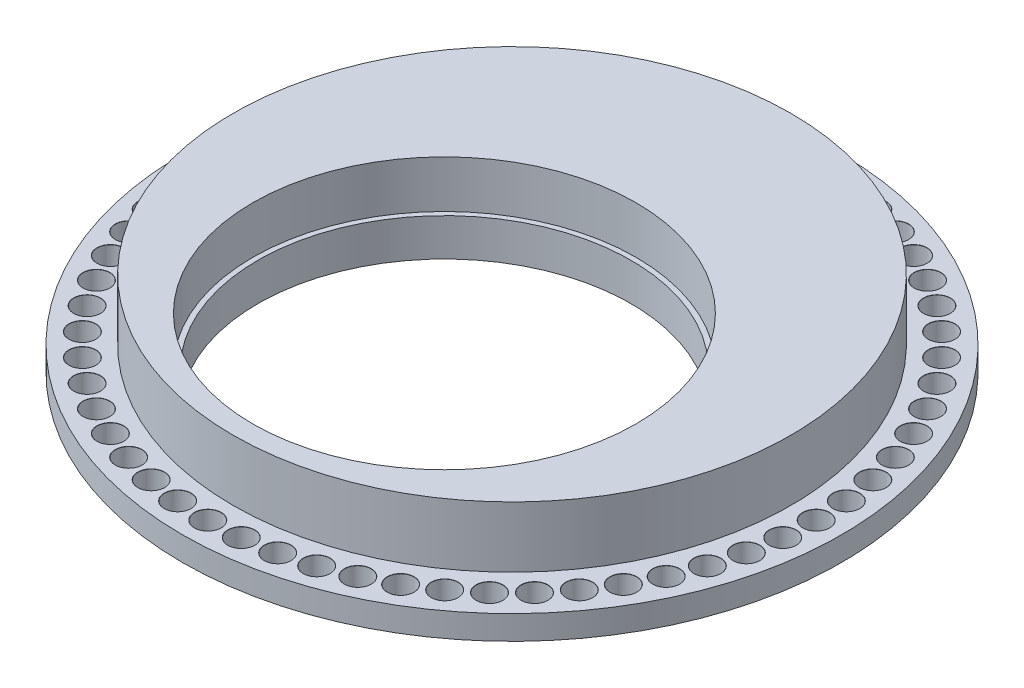
SolidWorks part; units mm, degrees
material "7075-T6, Plate (SS)"
ref_plane "X-Y Datum" through (0, 0, 0) normal (0, 0, 1) x (1, 0, 0)
ref_plane "X-Z Datum" through (0, 0, 0) normal (0, 1, 0) x (1, 0, 0)
ref_plane "Y-Z Datum" through (0, 0, 0) normal (1, 0, 0) x (0, 0, -1)
sketch "Sketch1" plane through (0, 0, 0) normal (0, 1, 0) x (1, 0, 0)
  line L0 (0, 0) -> (0, -12.7) construction
  line L1 (0, -43.0151) -> (0, 43.0151) construction
  line L2 (0, 61.9125) -> (0, 52.3875)
  circle A0 centre (0, -12.7) radius 35.052
  circle A1 centre (0, 0) radius 52.3875 construction
  circle A2 centre (0, 0) radius 57.15 construction
  circle A3 centre (0, 0) radius 61.9125
  point P12 (0, 57.15)
  dimension "D2" = 70.104
  dimension "D3" = 104.775
  dimension "D4" = 123.825
  dimension "D5" = 114.3
  dimension "D1" = 12.7
extrude "Boss-Extrude1" add sketch "Sketch1" along normal blind 4.5212
sketch "Sketch3" plane through (0, 4.5212, 0) normal (0, 1, 0) x (1, 0, 0)
  circle A0 centre (0, 0) radius 52.3875 construction
  circle A1 centre (0, 0) radius 52.3875
extrude "Boss-Extrude2" add sketch "Sketch3" along normal blind 11.43
sketch "Sketch4" plane through (0, 0, 0) normal (0, -1, 0) x (1, 0, 0)
  circle A0 centre (0, 12.7) radius 35.052 construction
  circle A1 centre (0, 12.7) radius 35.052
extrude "Cut-Extrude1" cut sketch "Sketch4" against normal through all
sketch "Sketch9" plane through (0, 15.9512, 0) normal (0, 1, 0) x (1, 0, 0)
  circle A0 centre (0, -12.7) radius 35.052 construction
  circle A1 centre (0, -12.7) radius 35.052 construction
  circle A2 centre (0, -12.7) radius 36
  dimension "D1" = 72
extrude "Cut-Extrude3" cut sketch "Sketch9" against normal blind 8.89
hole_wizard "Ø5.0mm Dowel Hole1" positions "Sketch7" profile "Sketch8" hole size "Ø5.0" standard "ANSI Metric" end condition through all
sketch "Sketch7" plane through (0, 4.5212, 0) normal (0, 1, 0) x (1, 0, 0)
  point P0 (0, 57.15)
sketch "Sketch8" plane through (0, 4.5212, -57.15) normal (1, 0, 0) x (0, 0, 1)
  line L0 (0, 0) -> (0, 4.5212)
  line L1 (0, 4.5212) -> (2.5, 4.5212)
  line L2 (2.5, 4.5212) -> (2.5, 0.025)
  line L3 (2.5, 0.025) -> (2.525, 0)
  line L5 (2.525, 0) -> (0, 0)
  line L6 (-2.5, 0.025) -> (-2.525, 0) construction
  line L11 (0, -6.35) -> (0, 107.95) construction
  dimension "Thru Hole Dia." = 5
  dimension "Thru Hole Depth" = 4.5212
  dimension "Near C'Sink Dia." = 5.05
  dimension "Near C'Sink Angle" = 90
pattern_circular "CirPattern1" count 60 over 360 about axis through (0, 0, 0) along (0, 1, 0) of "Ø5.0mm Dowel Hole1"
